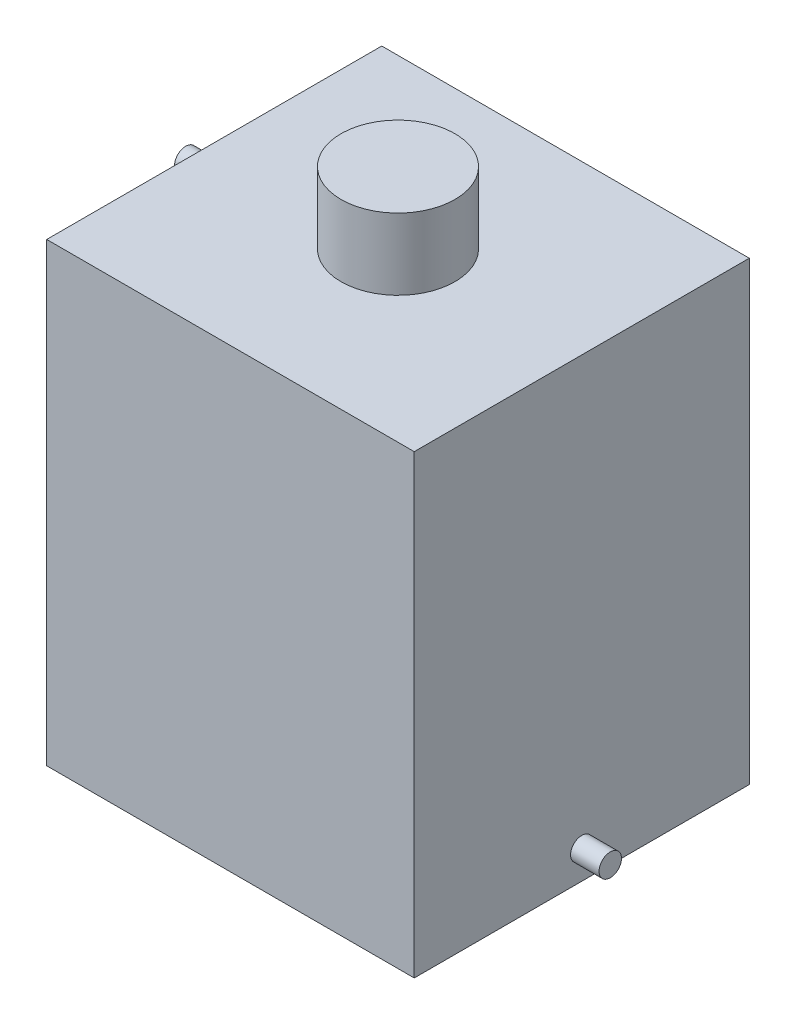
SolidWorks part; units mm, degrees
ref_plane "X-Y Datum" through (0, 0, 0) normal (0, 0, 1) x (1, 0, 0)
ref_plane "X-Z Datum" through (0, 0, 0) normal (0, 1, 0) x (1, 0, 0)
ref_plane "Y-Z Datum" through (0, 0, 0) normal (1, 0, 0) x (0, 0, -1)
sketch "Sketch1" plane through (0, 0, 0) normal (0, 1, 0) x (1, 0, 0)
  line L1 (81.915, 74.676) -> (-81.915, 74.676)
  line L2 (81.915, 74.676) -> (81.915, -74.676)
  line L3 (81.915, -74.676) -> (-81.915, -74.676)
  line L4 (-81.915, 74.676) -> (-81.915, -74.676)
  line L5 (81.915, 74.676) -> (-81.915, -74.676) construction
  line L6 (81.915, -74.676) -> (-81.915, 74.676) construction
  point P0 (0, 0)
  dimension "D1" = 163.83
  dimension "D2" = 149.352
extrude "Boss-Extrude1" add sketch "Sketch1" along normal blind 203.2
sketch "Sketch2" plane through (0, 203.2, 0) normal (0, 1, 0) x (1, 0, 0)
  circle A0 centre (0, 0) radius 25.4
  dimension "D1" = 50.8
extrude "Boss-Extrude2" add sketch "Sketch2" along normal blind 31.75
sketch "Sketch3" plane through (-81.915, 0, 0) normal (-1, 0, 0) x (0, 0, 1)
  line L0 (-74.676, 203.2) -> (74.676, 203.2) construction
  line L1 (-74.676, 203.2) -> (74.676, 203.2) construction
  line L2 (0, 203.2) -> (0, 0) construction
  line L3 (-74.676, 0) -> (74.676, 0) construction
  circle A0 centre (0, 190.5) radius 5
  point P8 (0, 0)
  dimension "D2" = 10
  dimension "D1" = 12.7
extrude "Boss-Extrude3" add sketch "Sketch3" along normal blind 12.7
sketch "Sketch5" plane through (81.915, 0, 0) normal (1, 0, 0) x (0, 0, -1)
  line L0 (-74.676, 0) -> (74.676, 0) construction
  line L1 (-74.676, 0) -> (74.676, 0) construction
  line L2 (0, 0) -> (0, 203.2) construction
  line L3 (-74.676, 203.2) -> (74.676, 203.2) construction
  circle A0 centre (0, 12.7) radius 5
  dimension "D1" = 10
  dimension "D2" = 12.7
extrude "Boss-Extrude4" add sketch "Sketch5" along normal blind 12.7
